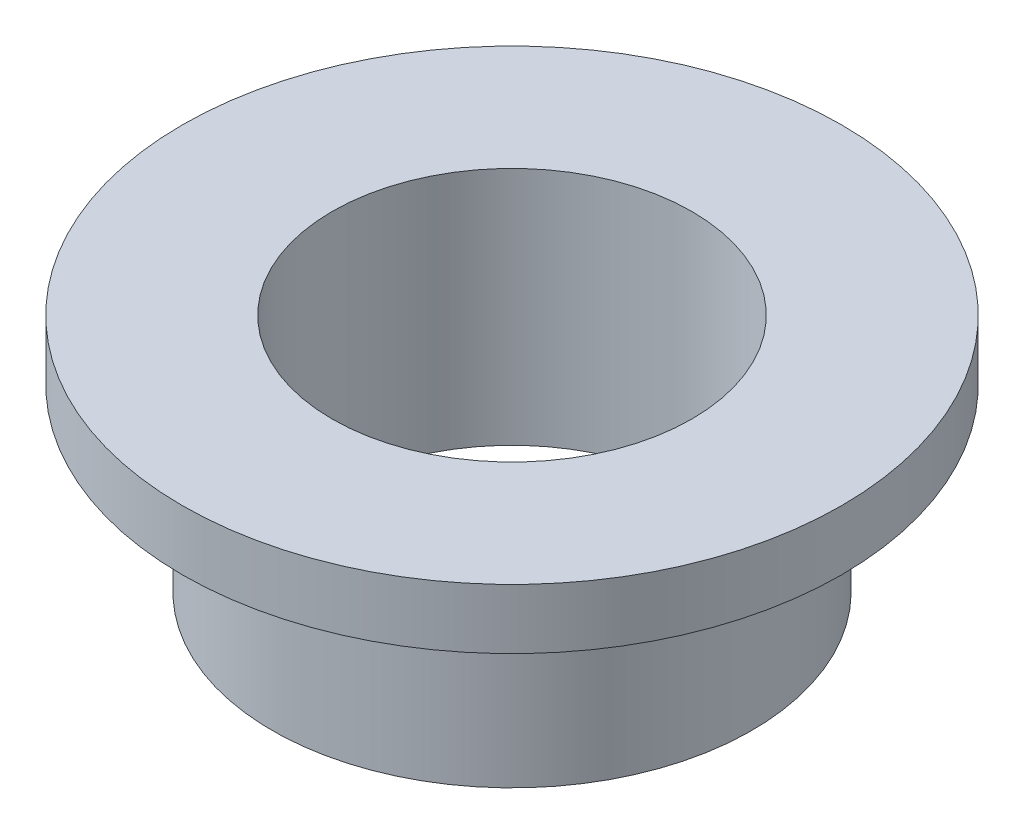
SolidWorks part; units mm, degrees
material "Tin Bearing Bronze"
ref_plane "Front Plane" through (0, 0, 0) normal (0, 0, 1) x (1, 0, 0)
ref_plane "Top Plane" through (0, 0, 0) normal (0, 1, 0) x (1, 0, 0)
ref_plane "Right Plane" through (0, 0, 0) normal (1, 0, 0) x (0, 0, -1)
sketch "Sketch1" plane through (0, 0, 0) normal (0, 1, 0) x (1, 0, 0)
  circle A0 centre (0, 0) radius 4.7625
  circle A1 centre (0, 0) radius 6.35
  dimension "D1" = 9.525
  dimension "D2" = 12.7
extrude "Boss-Extrude1" add sketch "Sketch1" along normal blind 4.7625
sketch "Sketch2" plane through (0, 4.7625, 0) normal (0, 1, 0) x (1, 0, 0)
  circle A0 centre (0, 0) radius 4.7625
  circle A1 centre (0, 0) radius 8.7312
  circle A2 centre (0, 0) radius 4.7625 construction
  dimension "D1" = 17.4625
extrude "Boss-Extrude2" add sketch "Sketch2" along normal blind 1.5875
